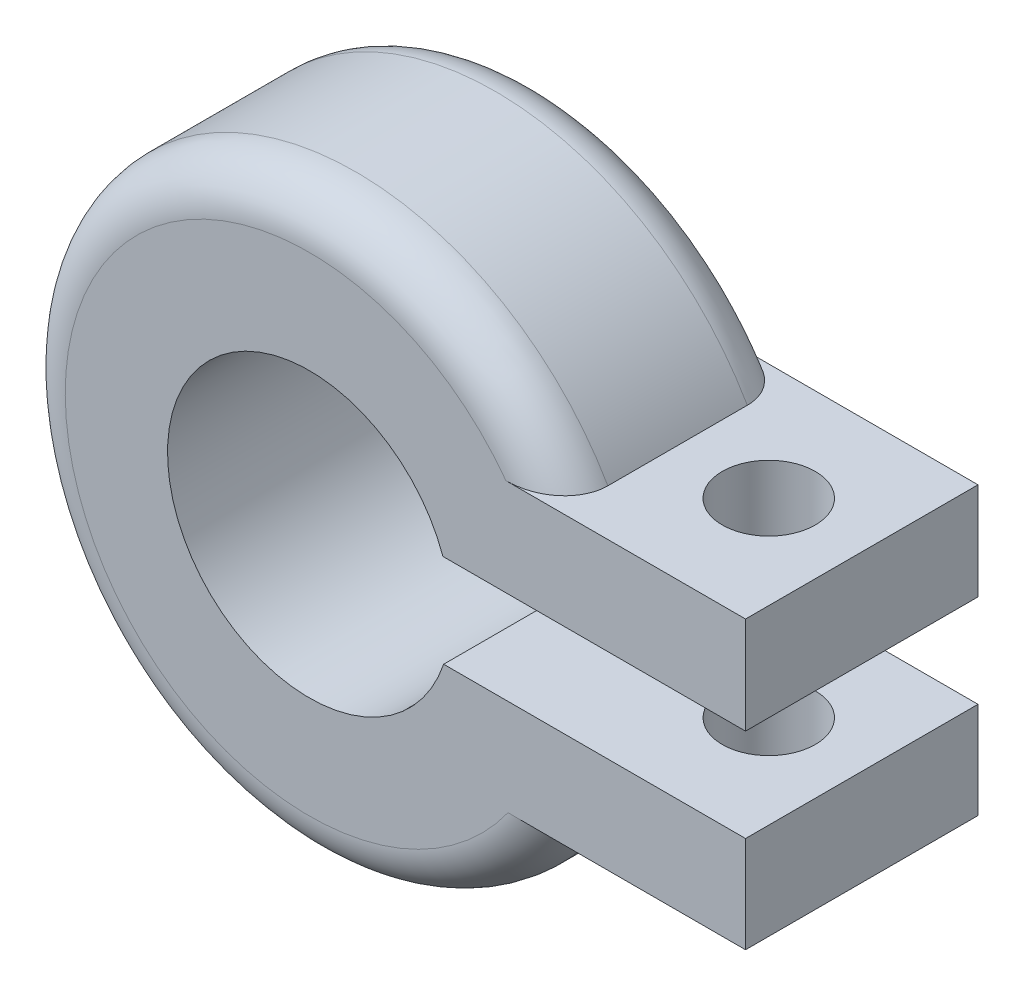
SolidWorks part; units mm, degrees
ref_plane "Front Plane" through (0, 0, 0) normal (1, 0, 0) x (0, 1, 0)
ref_plane "Top Plane" through (0, 0, 0) normal (0, 0, 1) x (0, 1, 0)
ref_plane "Right Plane" through (0, 0, 0) normal (0, 1, 0) x (-1, 0, 0)
sketch "Sketch1" plane through (0, 0, 0) normal (0, 0, 1) x (0, 1, 0)
  line L0 (-0.9771, -2.8892) -> (-0.9771, -6.1184)
  line L1 (1.0229, -2.8734) -> (1.0229, -6.1043)
  line L2 (-3.05, -5.4553) -> (-3.05, -9.3817)
  line L3 (-3.05, -9.3817) -> (-0.9771, -9.3817)
  line L4 (3.1115, -9.3817) -> (3.1115, -5.4204)
  line L5 (-0.9771, -6.1184) -> (-0.9771, -9.3817)
  line L6 (1.0229, -6.1043) -> (1.0229, -9.3817)
  line L7 (1.0229, -9.3817) -> (3.1115, -9.3817)
  arc A0 (1.0229, -2.8734) -> (-0.9771, -2.8892) centre (0, 0) ccw
  arc A1 (3.1115, -5.4204) -> (-3.05, -5.4553) centre (0, 0) ccw
  dimension "D1" = 6.1
  dimension "D2" = 12.5
  dimension "D3" = 2
extrude "Boss-Extrude1" add sketch "Sketch1" along normal blind 5
sketch "Sketch2" plane through (0, -0.9771, 0) normal (0, 1, 0) x (-1, 0, 0)
  line L1 (-9.3817, 5) -> (-9.3817, 0) construction
  line L2 (-9.3817, 5) -> (-5.4204, 5) construction
  circle A0 centre (-7.3817, 2.5) radius 1
  dimension "D1" = 2
  dimension "D2" = 2
  dimension "D3" = 2.5
fillet "Fillet3" radius 1 1 edges at (-6.2499, -0.0353, 5)
fillet "Fillet4" radius 1 1 edges at (-6.2499, -0.0353, 0)
extrude "Cut-Extrude1" cut sketch "Sketch2" against normal through all both and the other way through all
